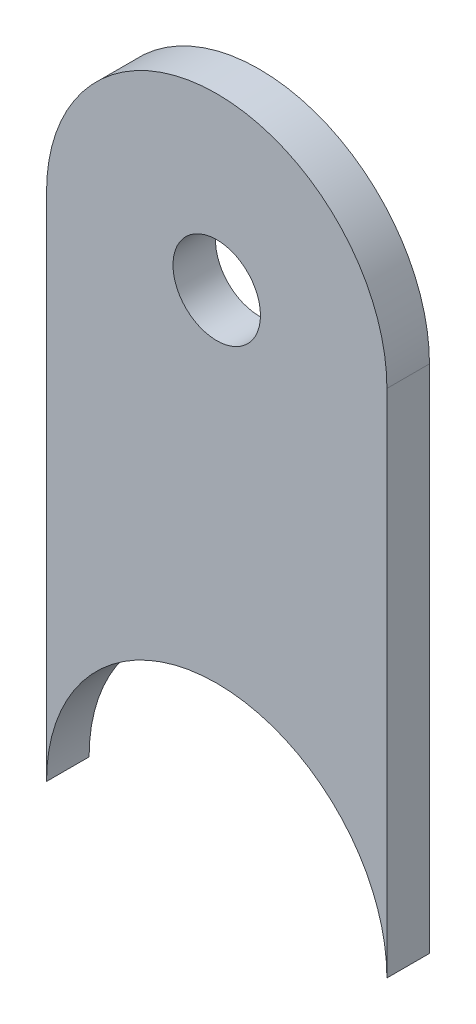
SolidWorks part; units mm, degrees
ref_plane "Front Plane" through (0, 0, 0) normal (0, 0, 1) x (1, 0, 0)
ref_plane "Top Plane" through (0, 0, 0) normal (0, 1, 0) x (1, 0, 0)
ref_plane "Right Plane" through (0, 0, 0) normal (1, 0, 0) x (0, 0, -1)
sketch "Sketch1" plane through (0, 0, 0) normal (0, 0, 1) x (1, 0, 0)
  line L0 (0, 0) -> (0, 38.1)
  line L1 (0, 0) -> (25.4, 0)
  line L2 (25.4, 0) -> (25.4, 38.1)
  line L3 (12.7, 34.8361) -> (12.7, 0)
  arc A0 (0, 38.1) -> (25.4, 38.1) centre (12.7, 38.1) cw
  circle A1 centre (12.7, 38.1) radius 3.2639
  circle A2 centre (12.7, 0) radius 12.7
  point P7 (12.7, 0)
  dimension "D1" = 6.5278
  dimension "D2" = 25.4
  dimension "D3" = 38.1
extrude "Boss-Extrude1" add sketch "Sketch1" along normal blind 3.175 contours A2 L2 A0 L0 A1
